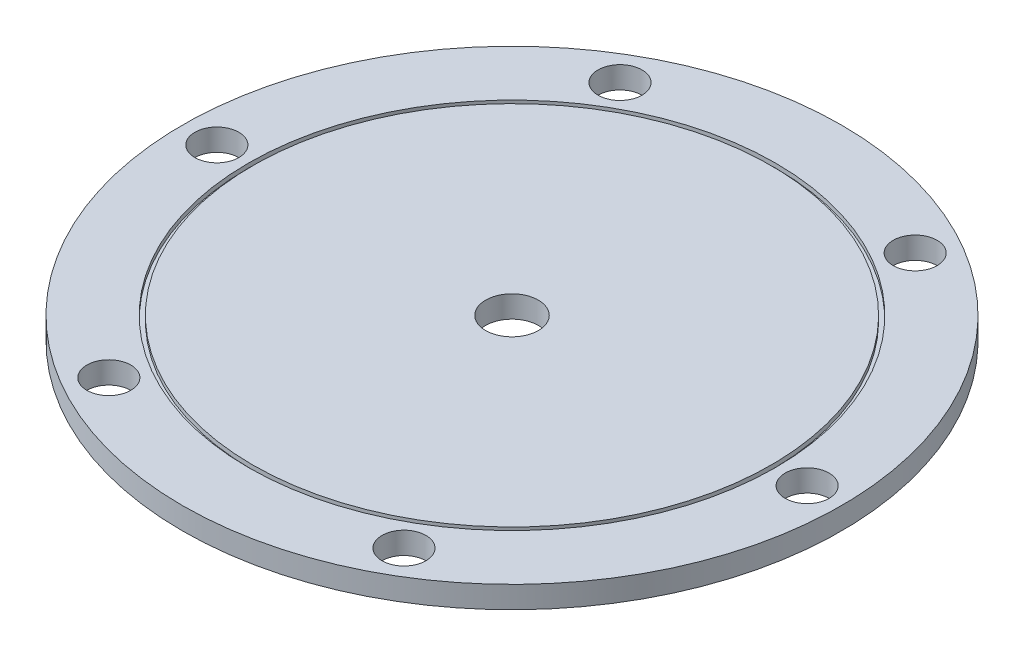
SolidWorks part; units mm, degrees
ref_plane "Front Plane" through (0, 0, 0) normal (0, 0, 1) x (1, 0, 0)
ref_plane "Top Plane" through (0, 0, 0) normal (0, 1, 0) x (1, 0, 0)
ref_plane "Right Plane" through (0, 0, 0) normal (1, 0, 0) x (0, 0, -1)
sketch "Sketch1" plane through (0, 0, 0) normal (0, 1, 0) x (1, 0, 0)
  circle A0 centre (0, 0) radius 75
extrude "Boss-Extrude1" add sketch "Sketch1" along normal blind 5
sketch "Sketch2" plane through (0, 5, 0) normal (0, 1, 0) x (1, 0, 0)
  circle A0 centre (0, 0) radius 60
  circle A1 centre (0, 0) radius 59
extrude "Cut-Extrude1" cut sketch "Sketch2" against normal blind 1
sketch "Sketch3" plane through (0, 5, 0) normal (0, 1, 0) x (1, 0, 0)
  circle A0 centre (-67.1671, 0) radius 5
extrude "Cut-Extrude2" cut sketch "Sketch3" against normal blind 161
pattern_circular "CirPattern2" count 6 over 360 about axis through (0, 0, 0) along (0, 1, 0) of "Cut-Extrude2"
sketch "Sketch4" plane through (0, 5, 0) normal (0, 1, 0) x (1, 0, 0)
  circle A0 centre (0, 0) radius 6
extrude "Cut-Extrude3" cut sketch "Sketch4" against normal blind 10
